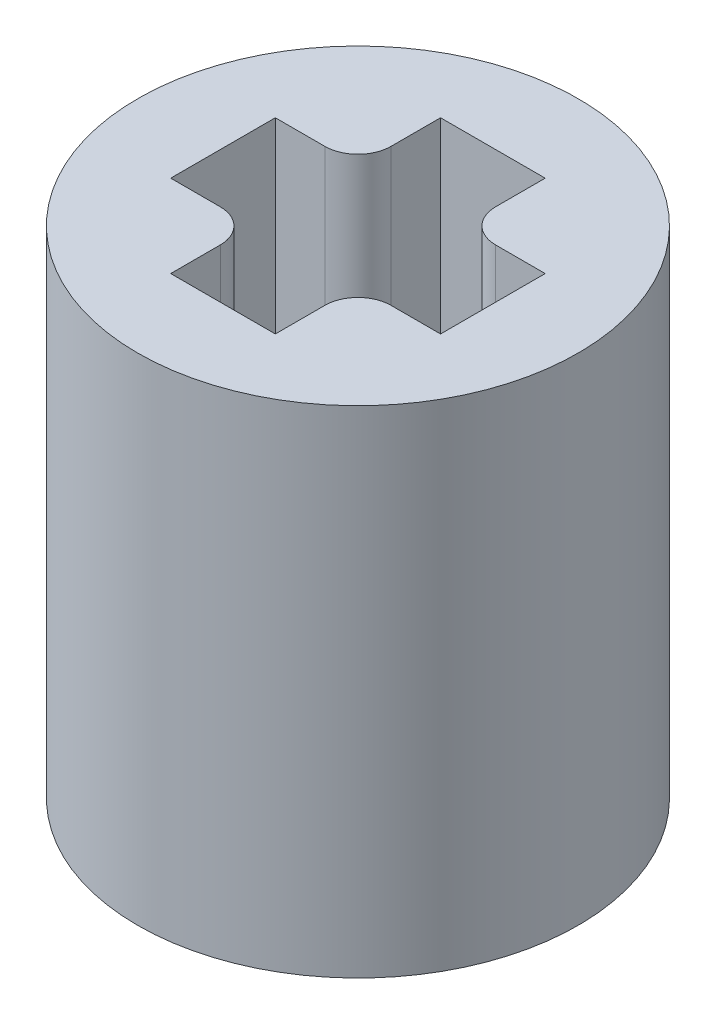
SolidWorks part; units mm, degrees
ref_plane "Front Plane" through (0, 0, 0) normal (0, 0, 1) x (1, 0, 0)
ref_plane "Top Plane" through (0, 0, 0) normal (0, 1, 0) x (1, 0, 0)
ref_plane "Right Plane" through (0, 0, 0) normal (1, 0, 0) x (0, 0, -1)
sketch "Sketch1" plane through (0, 0, 0) normal (0, 1, 0) x (1, 0, 0)
  circle A0 centre (0, 0) radius 4
  circle A1 centre (0, 0) radius 2.5
  dimension "D1" = 8
  dimension "D2" = 5
extrude "Boss-Extrude1" add sketch "Sketch1" along normal blind 4
sketch "Sketch3" plane through (0, 4, 0) normal (0, 1, 0) x (1, 0, 0)
  circle A0 centre (0, 0) radius 4
extrude "Boss-Extrude2" add sketch "Sketch3" along normal blind 5
sketch "Sketch4" plane through (0, 9, 0) normal (0, 1, 0) x (1, 0, 0)
  line L1 (-0.95, 2.45) -> (0.95, 2.45)
  line L2 (-0.95, 2.45) -> (-0.95, -2.45)
  line L3 (-0.95, -2.45) -> (0.95, -2.45)
  line L4 (0.95, 2.45) -> (0.95, -2.45)
  line L5 (-0.95, 2.45) -> (0.95, -2.45) construction
  line L6 (-0.95, -2.45) -> (0.95, 2.45) construction
  line L7 (-2.45, 0.95) -> (2.45, 0.95)
  line L8 (-2.45, 0.95) -> (-2.45, -0.95)
  line L9 (-2.45, -0.95) -> (2.45, -0.95)
  line L10 (2.45, 0.95) -> (2.45, -0.95)
  line L11 (-2.45, 0.95) -> (2.45, -0.95) construction
  line L12 (-2.45, -0.95) -> (2.45, 0.95) construction
  point P0 (0, 0)
  point P5 (0, 0)
  dimension "D1" = 1.9
  dimension "D2" = 4.9
  dimension "D3" = 4.9
  dimension "D4" = 1.9
extrude "Cut-Extrude1" cut sketch "Sketch4" against normal blind 4 contours L8 L9 L2 L7 | L2 L7 L4 L1 | L10 L7 L4 L9 | L2 L9 L4 L7 | L9 L2 L3 L4
fillet "Fillet1" radius 0.6 4 edges at (-0.95, 7, 0.95) (-0.95, 7, -0.95) (0.95, 7, 0.95) (0.95, 7, -0.95)
